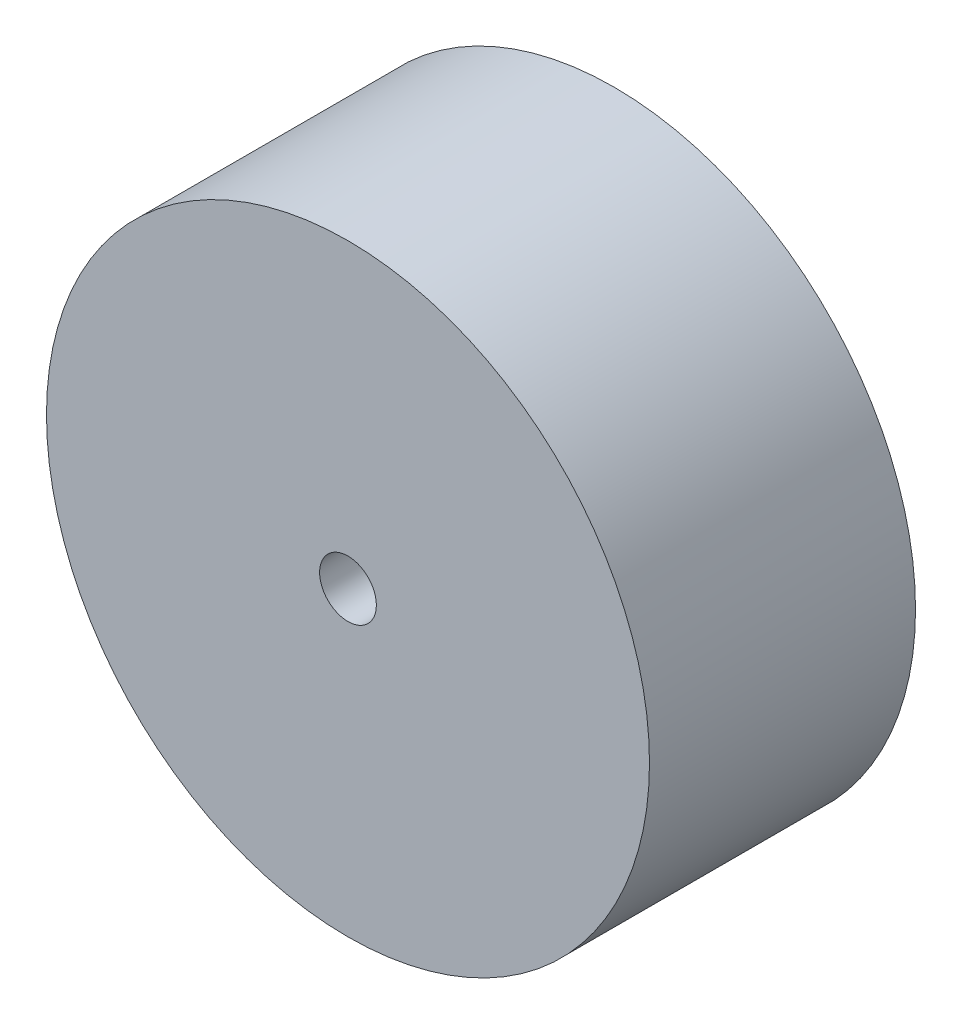
SolidWorks part; units mm, degrees
ref_plane "Front Plane" through (0, 0, 0) normal (0, 0, 1) x (1, 0, 0)
ref_plane "Top Plane" through (0, 0, 0) normal (0, 1, 0) x (1, 0, 0)
ref_plane "Right Plane" through (0, 0, 0) normal (1, 0, 0) x (0, 0, -1)
sketch "Sketch1" plane through (0, 0, 0) normal (0, 0, 1) x (1, 0, 0)
  circle A0 centre (0, 0) radius 17
  circle A1 centre (0, 0) radius 1.6
  dimension "D1" = 34
  dimension "D2" = 3.2
extrude "Boss-Extrude1" add sketch "Sketch1" along normal blind 15
